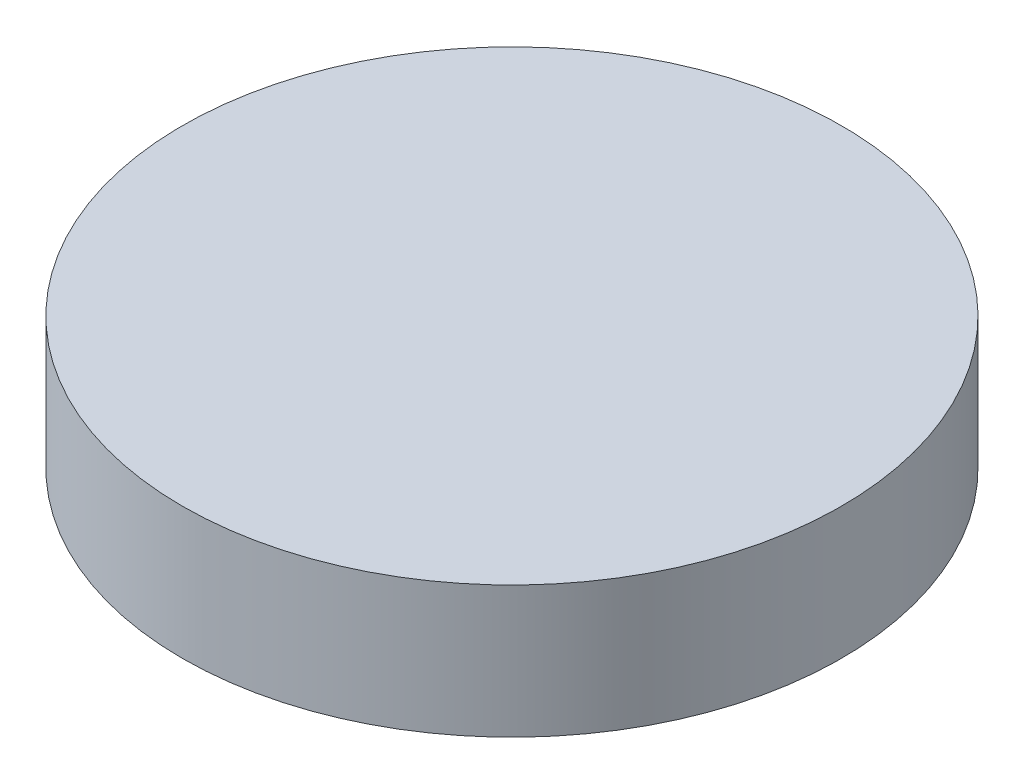
SolidWorks part; units mm, degrees
ref_plane "Front Plane" through (0, 0, 0) normal (0, 0, 1) x (1, 0, 0)
ref_plane "Top Plane" through (0, 0, 0) normal (0, 1, 0) x (1, 0, 0)
ref_plane "Right Plane" through (0, 0, 0) normal (1, 0, 0) x (0, 0, -1)
sketch "Sketch1" plane through (0, 0, 0) normal (0, 1, 0) x (1, 0, 0)
  circle A0 centre (0, 0) radius 8
  dimension "D1" = 16
extrude "Boss-Extrude1" add sketch "Sketch1" along normal blind 3.2
